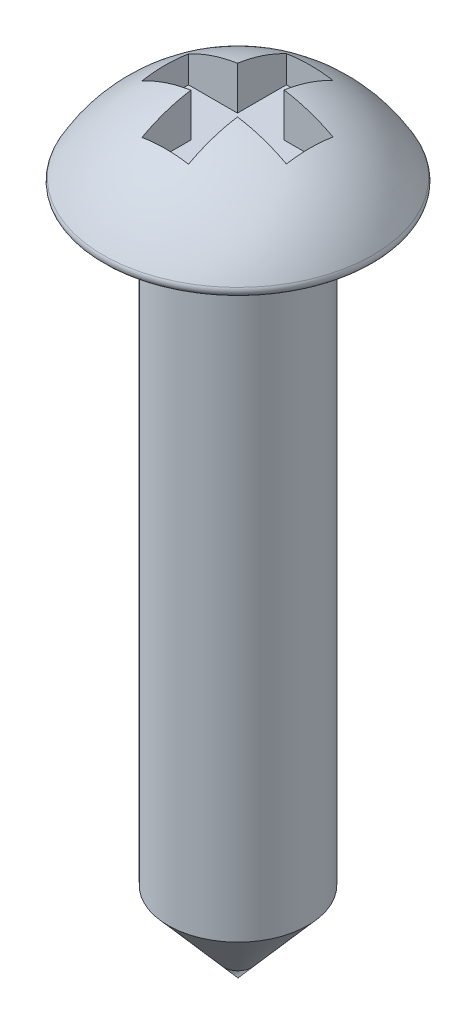
SolidWorks part; units mm, degrees
ref_plane "Plan de face" through (0, 0, 0) normal (0, 0, 1) x (1, 0, 0)
ref_plane "Plan de dessus" through (0, 0, 0) normal (0, 1, 0) x (1, 0, 0)
ref_plane "Plan de droite" through (0, 0, 0) normal (1, 0, 0) x (0, 0, -1)
sketch "Esquisse1" plane through (0, 0, 0) normal (0, 0, 1) x (1, 0, 0)
  line L0 (0, 3.8001) -> (0, -10.7655) construction
  line L1 (2.2, 0) -> (1.1, 0)
  line L2 (1.1, 0) -> (1.1, -9.5)
  line L3 (1.1, -9.5) -> (0, -10.7655)
  line L4 (0, -10.7655) -> (0, 1.393)
  arc A0 (2.2, 0) -> (0, 1.393) centre (0, -1.0408) ccw
  dimension "D4" = 40.997
  dimension "D1" = 1.1
  dimension "D2" = 9.5
  dimension "D3" = 2.2
revolve "Révolution1" add sketch "Esquisse1" angle 360 about L0
fillet "Congé1" radius 0.1 1 edges at (-2.2, 0, 0)
ref_plane "Plan1" through (0, 1.1565, 0) normal (0, 1, 0) x (-1, 0, 0)
sketch "Esquisse2" plane through (0, 1.1565, 0) normal (0, 1, 0) x (-1, 0, 0)
  line L0 (0.0048, 1.1408) -> (0.0048, 0.0036) construction
  line L1 (-0.3619, 1.1408) -> (0.3716, 1.1408)
  line L2 (-0.3619, 1.1408) -> (-0.3619, 0.3704)
  line L3 (-0.3619, -1.1335) -> (0.3716, -1.1335)
  line L4 (0.3716, 1.1408) -> (0.3716, 0.3704)
  line L5 (-1.1323, 0.3704) -> (-0.3619, 0.3704)
  line L6 (-1.1323, 0.3704) -> (-1.1323, -0.3632)
  line L7 (-1.1323, -0.3632) -> (-0.3619, -0.3632)
  line L8 (1.142, 0.3704) -> (1.142, -0.3632)
  line L9 (0.0048, 0.0036) -> (0.0048, -1.1335) construction
  line L10 (1.142, 0.0036) -> (0.0048, 0.0036) construction
  line L11 (0.0048, 0.0036) -> (-1.1323, 0.0036) construction
  line L12 (0.3716, -0.3632) -> (1.142, -0.3632)
  line L13 (-0.3619, -0.3632) -> (-0.3619, -1.1335)
  line L14 (0.3716, 0.3704) -> (1.142, 0.3704)
  line L15 (0.3716, -0.3632) -> (0.3716, -1.1335)
extrude "Enlèv. mat.-Extru.1" cut sketch "Esquisse2" against normal mid plane 1
